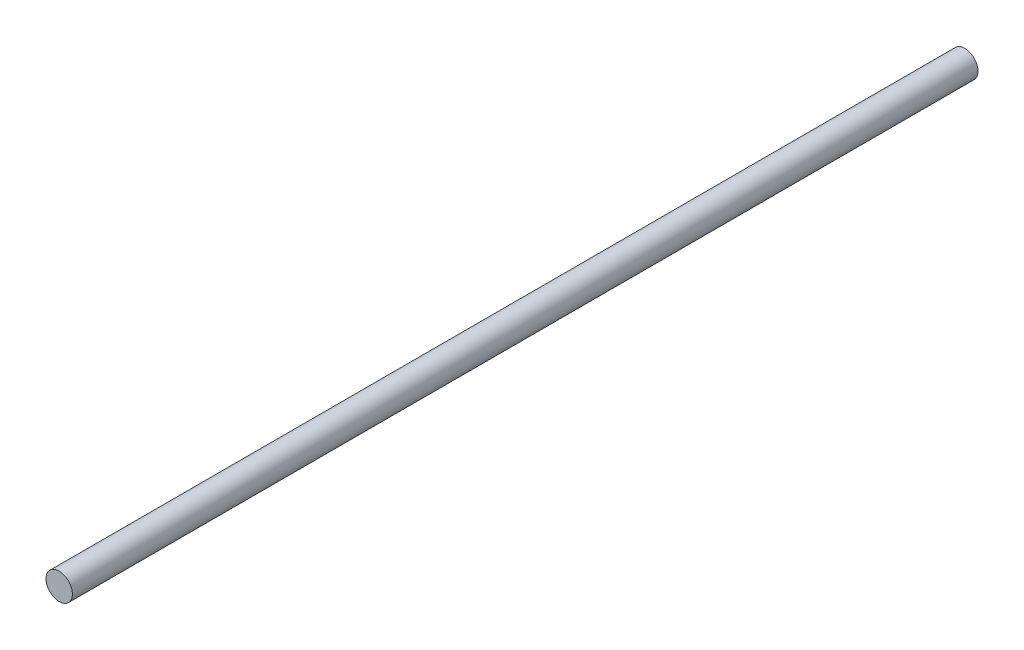
SolidWorks part; units mm, degrees
ref_plane "Ön Düzlem" through (0, 0, 0) normal (0, 0, 1) x (1, 0, 0)
ref_plane "Üst Düzlem" through (0, 0, 0) normal (0, 1, 0) x (1, 0, 0)
ref_plane "Sağ Düzlem" through (0, 0, 0) normal (1, 0, 0) x (0, 0, -1)
sketch "Sketch1" plane through (0, 0, 0) normal (0, 0, 1) x (1, 0, 0)
  circle A1 centre (0, 0) radius 3.5
  dimension "D2" = 7
extrude "Boss-Extrude1" add sketch "Sketch1" along normal blind 240
